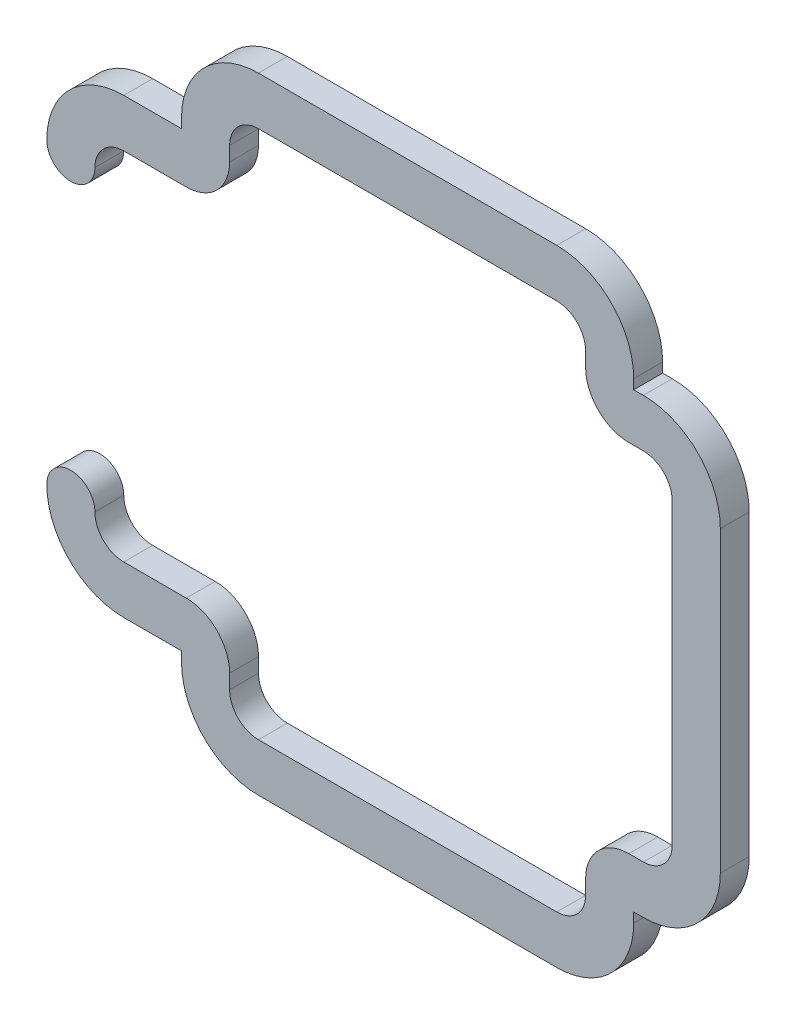
SolidWorks part; units mm, degrees
ref_plane "Plano frontal" through (0, 0, 0) normal (0, 0, 1) x (1, 0, 0)
ref_plane "Plano superior" through (0, 0, 0) normal (0, 1, 0) x (1, 0, 0)
ref_plane "Plano direito" through (0, 0, 0) normal (1, 0, 0) x (0, 0, -1)
sketch "Esboço1" plane through (0, 0, 0) normal (0, 0, 1) x (1, 0, 0)
  line L0 (-38.5, -4.5) -> (-7.5, -4.5)
  line L1 (-4.5, -1.5) -> (-4.5, 0)
  line L2 (0, 4.5) -> (1.5, 4.5)
  line L3 (4.5, 7.5) -> (4.5, 38.5)
  line L4 (1.5, 41.5) -> (0, 41.5)
  line L5 (-4.5, 46) -> (-4.5, 47.5)
  line L6 (-7.5, 50.5) -> (-38.5, 50.5)
  line L7 (-41.5, 47.5) -> (-41.5, 46)
  line L8 (-46, 41.5) -> (-52.5, 41.5)
  line L10 (-52.5, 4.5) -> (-46, 4.5)
  line L11 (-41.5, 0) -> (-41.5, -1.5)
  line L12 (-38.5, -9.5) -> (-7.5, -9.5)
  line L13 (0.5, -1.5) -> (0.5, -0.5)
  line L14 (0.5, -0.5) -> (1.5, -0.5)
  line L15 (9.5, 7.5) -> (9.5, 38.5)
  line L16 (1.5, 46.5) -> (0.5, 46.5)
  line L17 (0.5, 46.5) -> (0.5, 47.5)
  line L18 (-7.5, 55.5) -> (-38.5, 55.5)
  line L19 (-46.5, 47.5) -> (-46.5, 46.5)
  line L20 (-46.5, 46.5) -> (-52.5, 46.5)
  line L21 (-60.5, 38.5) -> (-60.5, 7.5)
  line L22 (-52.5, -0.5) -> (-46.5, -0.5)
  line L23 (-46.5, -0.5) -> (-46.5, -1.5)
  line L24 (-38.5, -9.5) -> (-7.5, -9.5)
  line L25 (0.5, -1.5) -> (0.5, -0.5)
  line L26 (0.5, -0.5) -> (1.5, -0.5)
  line L27 (9.5, 7.5) -> (9.5, 38.5)
  line L28 (1.5, 46.5) -> (0.5, 46.5)
  line L29 (0.5, 46.5) -> (0.5, 47.5)
  line L30 (-7.5, 55.5) -> (-38.5, 55.5)
  line L31 (-46.5, 47.5) -> (-46.5, 46.5)
  line L32 (-46.5, 46.5) -> (-52.5, 46.5)
  line L34 (-52.5, -0.5) -> (-46.5, -0.5)
  line L35 (-46.5, -0.5) -> (-46.5, -1.5)
  line L36 (-52.5, 4.5) -> (-41.5, 4.5) construction
  line L37 (-41.5, 4.5) -> (-41.5, -1.5) construction
  line L38 (-4.5, -1.5) -> (-4.5, 4.5) construction
  line L39 (-4.5, 4.5) -> (1.5, 4.5) construction
  line L40 (1.5, 41.5) -> (-4.5, 41.5) construction
  line L41 (-4.5, 41.5) -> (-4.5, 47.5) construction
  line L42 (-41.5, 47.5) -> (-41.5, 41.5) construction
  line L43 (-41.5, 41.5) -> (-52.5, 41.5) construction
  line L44 (-55.5, 38.5) -> (-60.5, 38.5) construction
  line L45 (-60.5, 7.5) -> (-55.5, 7.5) construction
  line L47 (-60.5, 38.5) -> (-60.5, 7.5) construction
  line L48 (-55.5, 38.5) -> (-55.5, 7.5) construction
  arc A0 (-41.5, -1.5) -> (-38.5, -4.5) centre (-38.5, -1.5) ccw
  arc A1 (-7.5, -4.5) -> (-4.5, -1.5) centre (-7.5, -1.5) ccw
  arc A2 (1.5, 4.5) -> (4.5, 7.5) centre (1.5, 7.5) ccw
  arc A3 (4.5, 38.5) -> (1.5, 41.5) centre (1.5, 38.5) ccw
  arc A4 (-4.5, 47.5) -> (-7.5, 50.5) centre (-7.5, 47.5) ccw
  arc A5 (-38.5, 50.5) -> (-41.5, 47.5) centre (-38.5, 47.5) ccw
  arc A6 (-52.5, 41.5) -> (-55.5, 38.5) centre (-52.5, 38.5) ccw
  arc A7 (-55.5, 7.5) -> (-52.5, 4.5) centre (-52.5, 7.5) ccw
  arc A8 (-46.5, -1.5) -> (-38.5, -9.5) centre (-38.5, -1.5) ccw
  arc A9 (-7.5, -9.5) -> (0.5, -1.5) centre (-7.5, -1.5) ccw
  arc A10 (1.5, -0.5) -> (9.5, 7.5) centre (1.5, 7.5) ccw
  arc A11 (9.5, 38.5) -> (1.5, 46.5) centre (1.5, 38.5) ccw
  arc A12 (0.5, 47.5) -> (-7.5, 55.5) centre (-7.5, 47.5) ccw
  arc A13 (-38.5, 55.5) -> (-46.5, 47.5) centre (-38.5, 47.5) ccw
  arc A14 (-52.5, 46.5) -> (-60.5, 38.5) centre (-52.5, 38.5) ccw
  arc A15 (-60.5, 7.5) -> (-52.5, -0.5) centre (-52.5, 7.5) ccw
  arc A16 (-46.5, -1.5) -> (-38.5, -9.5) centre (-38.5, -1.5) ccw
  arc A17 (-7.5, -9.5) -> (0.5, -1.5) centre (-7.5, -1.5) ccw
  arc A18 (1.5, -0.5) -> (9.5, 7.5) centre (1.5, 7.5) ccw
  arc A19 (9.5, 38.5) -> (1.5, 46.5) centre (1.5, 38.5) ccw
  arc A20 (0.5, 47.5) -> (-7.5, 55.5) centre (-7.5, 47.5) ccw
  arc A21 (-38.5, 55.5) -> (-46.5, 47.5) centre (-38.5, 47.5) ccw
  arc A22 (-52.5, 46.5) -> (-60.5, 38.5) centre (-52.5, 38.5) ccw
  arc A23 (-60.5, 7.5) -> (-52.5, -0.5) centre (-52.5, 7.5) ccw
  arc A24 (-46, 4.5) -> (-41.5, 0) centre (-46, 0) cw
  arc A25 (-4.5, 0) -> (0, 4.5) centre (0, 0) cw
  arc A26 (0, 41.5) -> (-4.5, 46) centre (0, 46) cw
  arc A27 (-41.5, 46) -> (-46, 41.5) centre (-46, 46) cw
  arc A28 (-55.5, 7.5) -> (-60.5, 7.5) centre (-58, 7.5) ccw
  arc A29 (-60.5, 38.5) -> (-55.5, 38.5) centre (-58, 38.5) ccw
  dimension "D3" = 4.5
  dimension "D1" = 0
  dimension "D2" = 5
extrude "Ressalto-extrusão1" add sketch "Esboço1" along normal blind 3
